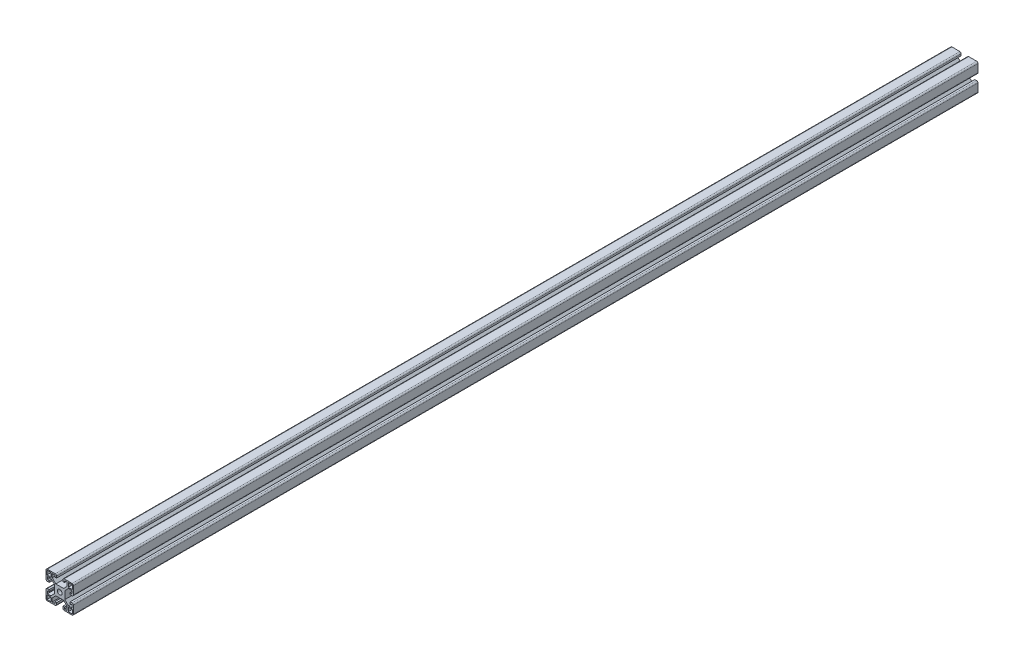
SolidWorks part; units mm, degrees
ref_plane "Alzado" through (0, 0, 0) normal (0, 0, 1) x (1, 0, 0)
ref_plane "Planta" through (0, 0, 0) normal (0, 1, 0) x (1, 0, 0)
ref_plane "Vista lateral" through (0, 0, 0) normal (1, 0, 0) x (0, 0, -1)
sketch "Croquis1" plane through (0, 0, 0) normal (0, 0, 1) x (1, 0, 0)
  line L1 (-20, -20) -> (20, -20)
  line L2 (-20, -20) -> (-20, 20)
  line L3 (-20, 20) -> (20, 20)
  line L4 (20, -20) -> (20, 20)
  line L5 (-20, -20) -> (20, 20) construction
  line L6 (-20, 20) -> (20, -20) construction
  point P0 (0, 0)
  dimension "D1" = 40
  dimension "D2" = 40
extrude "Saliente-Extruir1" add sketch "Croquis1" along normal blind 1320
sketch "Croquis2" plane through (0, 0, 1320) normal (0, 0, 1) x (1, 0, 0)
  line L0 (-7.5, 7.5) -> (-20, 20) construction
  line L1 (5.7336, -7.5014) -> (-5.7336, -7.5014)
  line L2 (7.5013, -5.7336) -> (7.5013, 5.7336)
  line L3 (5.7336, 7.5014) -> (-5.7336, 7.5014)
  line L4 (-7.5013, -5.7336) -> (-7.5013, 5.7336)
  line L5 (7.5, -7.5) -> (-7.5, 7.5) construction
  line L6 (7.5, 7.5) -> (-7.5, -7.5) construction
  line L7 (-5.7336, 7.5014) -> (-11, 12.7678)
  line L8 (-7.5013, 5.7336) -> (-12.7678, 11)
  line L9 (-20, 20) -> (-20, -20) construction
  line L10 (-18.5, 12.5) -> (-12.5, 12.5)
  line L11 (-18.5, 12.5) -> (-18.5, 18.5)
  line L12 (-18.5, 18.5) -> (-12.5, 18.5)
  line L13 (-12.5, 12.5) -> (-12.5, 18.5)
  line L14 (-18.5, 12.5) -> (-12.5, 18.5) construction
  line L15 (-18.5, 18.5) -> (-12.5, 12.5) construction
  line L16 (-11, 12.7678) -> (-11, 18)
  line L17 (-11, 18) -> (-7, 18)
  line L18 (-7, 18) -> (-7, 15.5)
  line L19 (-7, 15.5) -> (-4.5, 15.5)
  line L20 (-4.5, 15.5) -> (-4.5, 20)
  line L21 (20, 20) -> (-20, 20) construction
  line L22 (0, 20) -> (0, -20) construction
  line L23 (-20, -20) -> (20, -20) construction
  line L24 (-12.7678, 11) -> (-17.8676, 11)
  line L25 (-17.8676, 11) -> (-17.8676, 7)
  line L26 (-17.8676, 7) -> (-15.3676, 7)
  line L27 (-15.3676, 7) -> (-15.3676, 4.5)
  line L28 (-15.3676, 4.5) -> (-20, 4.5)
  line L29 (18.5, 18.5) -> (12.5, 12.5) construction
  line L30 (18.5, 12.5) -> (12.5, 18.5) construction
  line L31 (7.5, 7.5) -> (20, 20) construction
  line L32 (15.3676, 4.5) -> (20, 4.5)
  line L33 (15.3676, 7) -> (15.3676, 4.5)
  line L34 (17.8676, 7) -> (15.3676, 7)
  line L35 (17.8676, 11) -> (17.8676, 7)
  line L36 (12.7678, 11) -> (17.8676, 11)
  line L37 (4.5, 15.5) -> (4.5, 20)
  line L38 (7, 15.5) -> (4.5, 15.5)
  line L39 (7, 18) -> (7, 15.5)
  line L40 (11, 18) -> (7, 18)
  line L41 (11, 12.7678) -> (11, 18)
  line L42 (12.5, 12.5) -> (12.5, 18.5)
  line L43 (18.5, 18.5) -> (12.5, 18.5)
  line L44 (18.5, 12.5) -> (18.5, 18.5)
  line L45 (18.5, 12.5) -> (12.5, 12.5)
  line L46 (7.5013, 5.7336) -> (12.7678, 11)
  line L47 (5.7336, 7.5014) -> (11, 12.7678)
  line L48 (20, 0) -> (-20, 0) construction
  line L49 (20, -20) -> (20, 20) construction
  line L50 (7.5, -7.5) -> (20, -20) construction
  line L51 (18.5, -12.5) -> (12.5, -18.5) construction
  line L52 (18.5, -18.5) -> (12.5, -12.5) construction
  line L53 (-18.5, -18.5) -> (-12.5, -12.5) construction
  line L54 (-18.5, -12.5) -> (-12.5, -18.5) construction
  line L55 (-7.5, -7.5) -> (-20, -20) construction
  line L56 (5.7336, -7.5014) -> (11, -12.7678)
  line L57 (7.5013, -5.7336) -> (12.7678, -11)
  line L58 (18.5, -12.5) -> (12.5, -12.5)
  line L59 (18.5, -12.5) -> (18.5, -18.5)
  line L60 (18.5, -18.5) -> (12.5, -18.5)
  line L61 (12.5, -12.5) -> (12.5, -18.5)
  line L62 (11, -12.7678) -> (11, -18)
  line L63 (11, -18) -> (7, -18)
  line L64 (7, -18) -> (7, -15.5)
  line L65 (7, -15.5) -> (4.5, -15.5)
  line L66 (4.5, -15.5) -> (4.5, -20)
  line L67 (12.7678, -11) -> (17.8676, -11)
  line L68 (17.8676, -11) -> (17.8676, -7)
  line L69 (17.8676, -7) -> (15.3676, -7)
  line L70 (15.3676, -7) -> (15.3676, -4.5)
  line L71 (15.3676, -4.5) -> (20, -4.5)
  line L72 (-15.3676, -4.5) -> (-20, -4.5)
  line L73 (-15.3676, -7) -> (-15.3676, -4.5)
  line L74 (-17.8676, -7) -> (-15.3676, -7)
  line L75 (-17.8676, -11) -> (-17.8676, -7)
  line L76 (-12.7678, -11) -> (-17.8676, -11)
  line L77 (-4.5, -15.5) -> (-4.5, -20)
  line L78 (-7, -15.5) -> (-4.5, -15.5)
  line L79 (-7, -18) -> (-7, -15.5)
  line L80 (-11, -18) -> (-7, -18)
  line L81 (-11, -12.7678) -> (-11, -18)
  line L82 (-12.5, -12.5) -> (-12.5, -18.5)
  line L83 (-18.5, -18.5) -> (-12.5, -18.5)
  line L84 (-18.5, -12.5) -> (-18.5, -18.5)
  line L85 (-18.5, -12.5) -> (-12.5, -12.5)
  line L86 (-7.5013, -5.7336) -> (-12.7678, -11)
  line L87 (-5.7336, -7.5014) -> (-11, -12.7678)
  line L88 (5.7336, -7.5014) -> (-5.7336, -7.5014)
  line L89 (-20, -4.5) -> (-20, 4.5)
  line L90 (20, 4.5) -> (20, -4.5)
  line L91 (-4.5, -20) -> (4.5, -20)
  line L92 (-4.5, 20) -> (4.5, 20)
  circle A0 centre (0, 0) radius 3.5
  point P0 (0, 0)
  point P14 (-15.5, 15.5)
  point P56 (15.5, 15.5)
  point P99 (15.5, -15.5)
  point P100 (-15.5, -15.5)
  line M20 (20, -20) -> (20, 20)
  line M21 (20, 20) -> (-20, 20)
  line M22 (-20, 20) -> (-20, -20)
  line M23 (-20, -20) -> (20, -20)
  dimension "D3" = 7
  dimension "D1" = 15
  dimension "D2" = 15
  dimension "D4" = 1.25
  dimension "D5" = 1.25
  dimension "D6" = 1.5
  dimension "D7" = 6
  dimension "D8" = 6
  dimension "D9" = 1.5
  dimension "D10" = 2
  dimension "D11" = 4
  dimension "D12" = 2.5
  dimension "D13" = 2.5
  dimension "D14" = 1.5
  dimension "D15" = 4
  dimension "D16" = 2.5
  dimension "D17" = 2.5
extrude "Cortar-Extruir2" cut sketch "Croquis2" against normal up to surface (1320 mm away) contours L10 L13 L12 L11 | L3 L47 L41 L40 L39 L38 L37 L20 L19 L18 L17 L16 L7 M21 | L45 L44 L43 L42 | L70 L71 L32 L33 L34 L35 L36 L46 L2 L57 L67 L68 L69 M20 | L86 L4 L8 L24 L25 L26 L27 L28 L72 L73 L74 L75 L76 M22 | A0 | L1 L87 L81 L80 L79 L78 L77 L66 L65 L64 L63 L62 L56 M23 | L85 L84 L83 L82 | L58 L61 L60 L59 up to face at (0, 0, 0)
fillet "Redondeo1" radius 2 4 edges at (-20, -20, 660) (-20, 20, 660) (20, -20, 660) (20, 20, 660)
fillet "Redondeo2" radius 2 8 edges at (-20, -4.5, 660) (-20, 4.5, 660) (-4.5, -20, 660) (4.5, -20, 660) (20, 4.5, 660) (20, -4.5, 660) (4.5, 20, 660) (-4.5, 20, 660)
